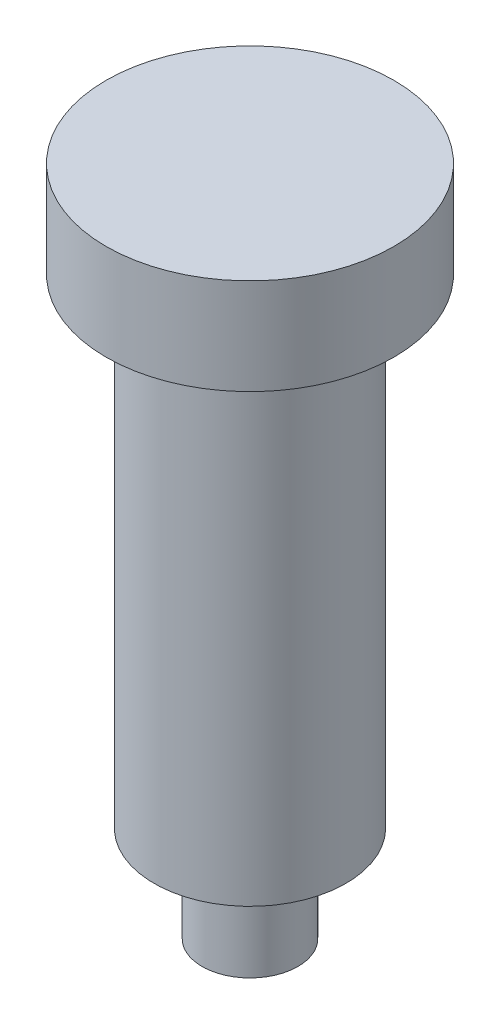
SolidWorks part; units mm, degrees
material "Plain Carbon Steel"
ref_plane "Front Plane" through (0, 0, 0) normal (0, 0, 1) x (1, 0, 0)
ref_plane "Top Plane" through (0, 0, 0) normal (0, 1, 0) x (1, 0, 0)
ref_plane "Right Plane" through (0, 0, 0) normal (1, 0, 0) x (0, 0, -1)
sketch "Sketch1" plane through (0, 0, 0) normal (0, 0, 1) x (1, 0, 0)
  line L0 (-0.6383, 15.9574) -> (5.3617, 15.9574)
  line L1 (5.3617, 15.9574) -> (5.3617, 11.9574)
  line L2 (5.3617, 11.9574) -> (3.3617, 11.9574)
  line L3 (3.3617, 11.9574) -> (3.3617, -8.0426)
  line L4 (3.3617, -8.0426) -> (1.3617, -8.0426)
  line L5 (1.3617, -8.0426) -> (1.3617, -12.0426)
  line L6 (1.3617, -12.0426) -> (-0.6383, -12.0426)
  line L7 (-0.6383, -12.0426) -> (-0.6383, 15.9574)
  dimension "D1" = 4
  dimension "D2" = 2
  dimension "D3" = 4
  dimension "D4" = 20
  dimension "D5" = 4
  dimension "D6" = 6
revolve "Revolve1" add sketch "Sketch1" angle 360 about L7
